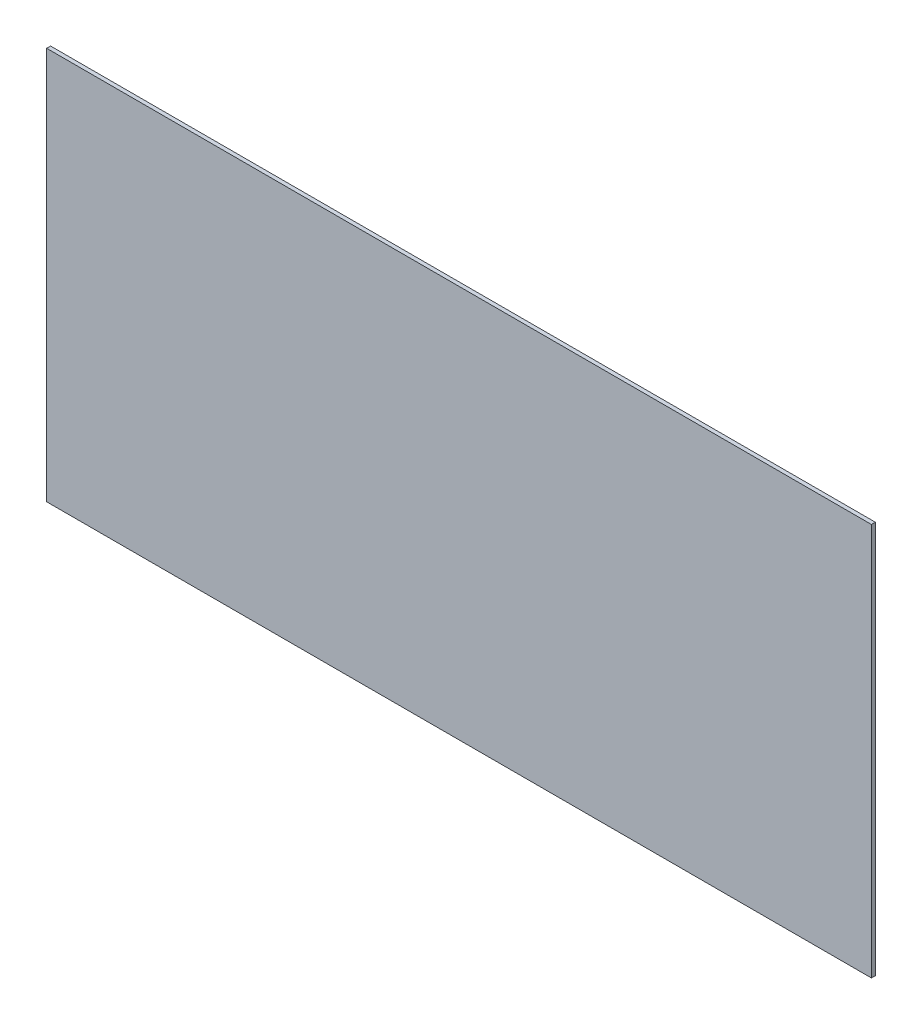
SolidWorks part; units mm, degrees
material "Дуб"
ref_plane "Спереди" through (0, 0, 0) normal (0, 0, 1) x (1, 0, 0)
ref_plane "Сверху" through (0, 0, 0) normal (0, 1, 0) x (1, 0, 0)
ref_plane "Справа" through (0, 0, 0) normal (1, 0, 0) x (0, 0, -1)
sketch "Эскиз1" plane through (0, 0, 0) normal (0, 0, 1) x (1, 0, 0)
  line L1 (0, 0) -> (2100, 0)
  line L2 (0, 0) -> (0, 1000)
  line L3 (0, 1000) -> (2100, 1000)
  line L4 (2100, 0) -> (2100, 1000)
  dimension "D1" = 2100
  dimension "D2" = 1000
extrude "Бобышка-Вытянуть1" add sketch "Эскиз1" along normal blind 10
sketch "Эскиз2" plane through (0, 0, 10) normal (0, 0, 1) x (1, 0, 0)
  line L0 (0, 1000) -> (0, 0) construction
  line L1 (150, 125) -> (850, 125)
  line L2 (150, 125) -> (150, 725)
  line L3 (150, 725) -> (850, 725)
  line L4 (850, 125) -> (850, 725)
  line L5 (2100, 1000) -> (0, 1000) construction
  dimension "D1" = 700
  dimension "D2" = 600
  dimension "D3" = 150
  dimension "D4" = 275
extrude "Вырез-Вытянуть1" [suppressed] cut sketch "Эскиз2" against normal through all
